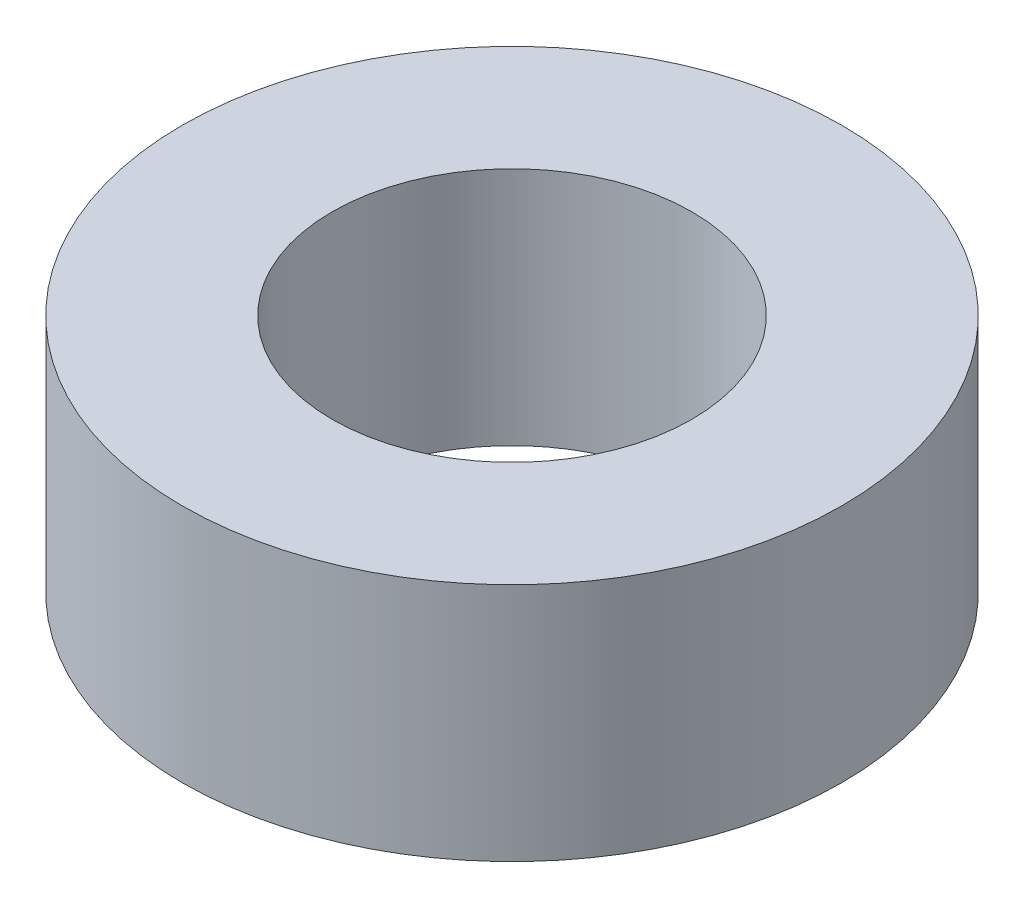
SolidWorks part; units mm, degrees
ref_plane "Front" through (0, 0, 0) normal (0, 0, 1) x (1, 0, 0)
ref_plane "Top" through (0, 0, 0) normal (0, 1, 0) x (1, 0, 0)
ref_plane "Right" through (0, 0, 0) normal (1, 0, 0) x (0, 0, -1)
sketch "Sketch1" plane through (0, 0, 0) normal (0, 1, 0) x (1, 0, 0)
  circle A0 centre (0, 0) radius 2.75
  circle A1 centre (0, 0) radius 1.5
  dimension "D1" = 5.5
  dimension "D2" = 3
extrude "Boss-Extrude1" add sketch "Sketch1" along normal blind 2
